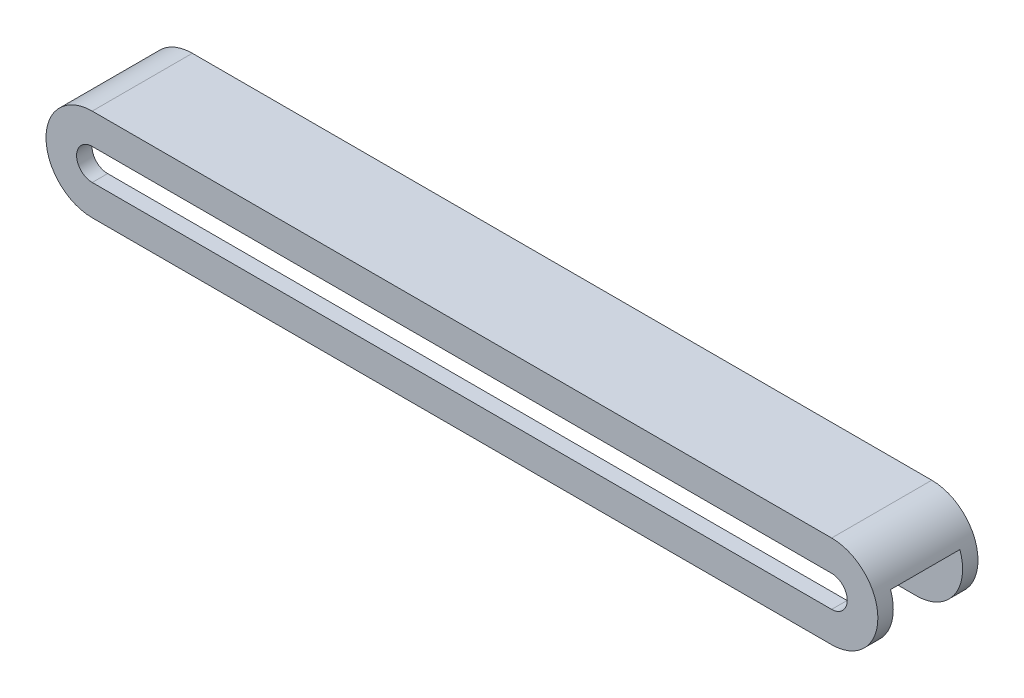
SolidWorks part; units mm, degrees
other "Markup1"
sketch "Sketch3" plane through (-19.05, 19.05, 41.275) normal (-0.6362, 0.6319, 0.4426) x (0.5294, -0.0598, 0.8463)
ref_plane "Front Plane" through (0, 0, 0) normal (0, 0, 1) x (1, 0, 0)
ref_plane "Top Plane" through (0, 0, 0) normal (0, 1, 0) x (1, 0, 0)
ref_plane "Right Plane" through (0, 0, 0) normal (1, 0, 0) x (0, 0, -1)
sketch "Sketch1" plane through (0, 0, 0) normal (0, 0, 1) x (1, 0, 0)
  line L0 (0, 0) -> (304.8, 0) construction
  line L1 (0, 6.4325) -> (304.8, 6.4325)
  line L2 (0, -6.4325) -> (304.8, -6.4325)
  line L3 (0, 0) -> (304.8, 0) construction
  line L4 (0, 19.05) -> (304.8, 19.05)
  line L5 (0, -19.05) -> (304.8, -19.05)
  arc A0 (0, 6.4325) -> (0, -6.4325) centre (0, 0) ccw
  arc A1 (304.8, -6.4325) -> (304.8, 6.4325) centre (304.8, 0) ccw
  arc A2 (0, 19.05) -> (0, -19.05) centre (0, 0) ccw
  arc A3 (304.8, -19.05) -> (304.8, 19.05) centre (304.8, 0) ccw
  point P3 (152.4, 0)
  point P10 (152.4, 0)
  dimension "D1" = 304.8
  dimension "D2" = 12.8651
  dimension "D3" = 38.1
extrude "Boss-Extrude1" add sketch "Sketch1" along normal blind 41.275
sketch "Sketch2" plane through (0, -19.05, 0) normal (0, -1, 0) x (1, 0, 0)
  line L0 (323.85, 0) -> (304.8, 0)
  line L1 (323.85, 0) -> (304.8, 0) construction
  line L2 (304.8, 0) -> (0, 0)
  line L3 (304.8, 0) -> (0, 0) construction
  line L4 (0, 0) -> (-19.05, 0)
  line L5 (304.8, 0) -> (-19.05, 0) construction
  line L6 (-19.05, 0) -> (-19.05, 41.275)
  line L7 (-19.05, 0) -> (-19.05, 41.275) construction
  line L8 (-19.05, 41.275) -> (0, 41.275)
  line L9 (-19.05, 41.275) -> (0, 41.275) construction
  line L10 (0, 41.275) -> (304.8, 41.275)
  line L11 (0, 41.275) -> (323.85, 41.275) construction
  line L12 (304.8, 41.275) -> (323.85, 41.275)
  line L13 (304.8, 41.275) -> (323.85, 41.275) construction
  line L14 (323.85, 41.275) -> (323.85, 0)
  line L15 (323.85, 41.275) -> (323.85, 0) construction
  line L16 (-19.05, 20.6375) -> (323.85, 20.6375) construction
  line L17 (323.85, 6.35) -> (-19.05, 6.35)
  line L18 (323.85, 6.35) -> (323.85, 34.925)
  line L19 (-19.05, 6.35) -> (-19.05, 34.925)
  line L20 (323.85, 34.925) -> (-19.05, 34.925)
  line L21 (323.85, 6.35) -> (-19.05, 34.925) construction
  line L22 (-19.05, 6.35) -> (323.85, 34.925) construction
  point P10 (0, 0)
  point P11 (152.4, 20.6375)
  point P12 (152.4, 20.6375)
  dimension "D1" = 28.575
extrude "Cut-Extrude1" cut sketch "Sketch2" against normal up to surface (25.4825 mm away) up to face at (152.4, 6.4325, 20.6375)
